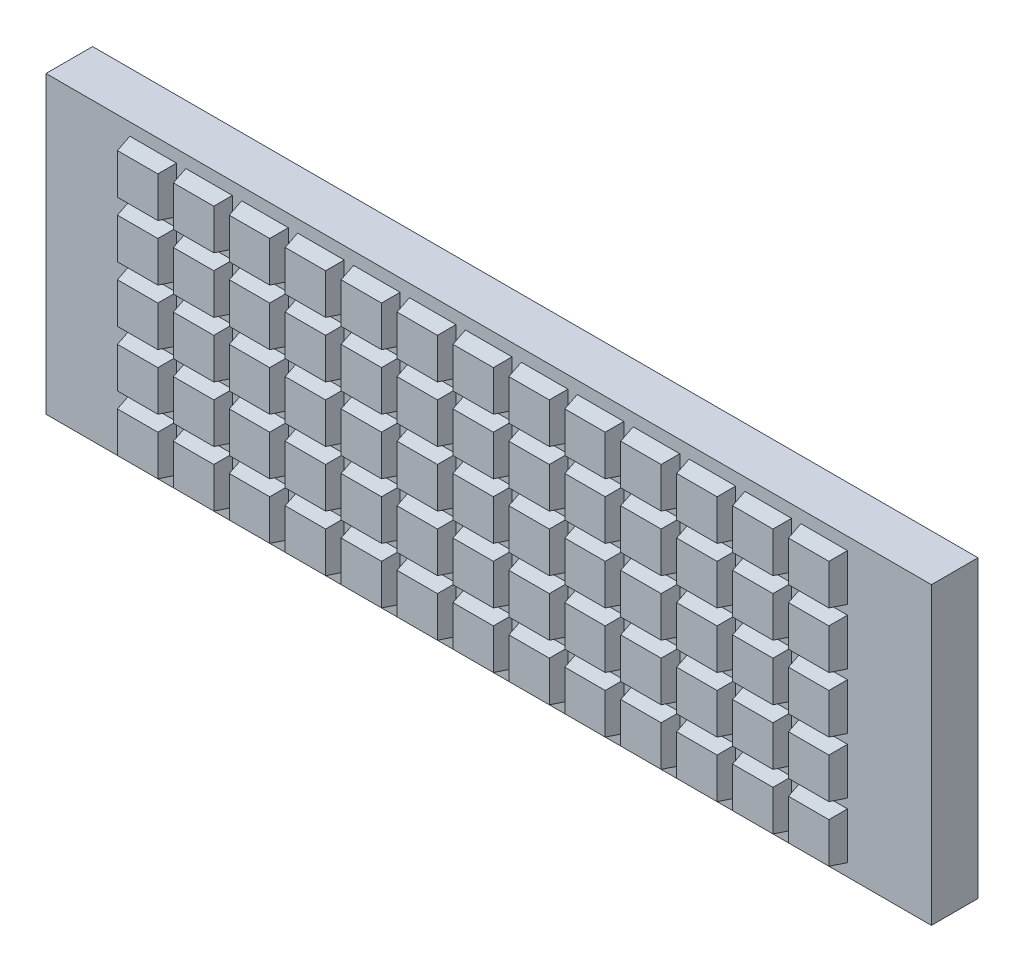
SolidWorks part; units mm, degrees
ref_plane "前视基准面" through (0, 0, 0) normal (0, 0, 1) x (1, 0, 0)
ref_plane "上视基准面" through (0, 0, 0) normal (0, 1, 0) x (1, 0, 0)
ref_plane "右视基准面" through (0, 0, 0) normal (1, 0, 0) x (0, 0, -1)
sketch "草图1" plane through (0, 0, 0) normal (0, 0, 1) x (1, 0, 0)
  line L0 (-142.5, -47.5) -> (142.5, -47.5)
  line L1 (142.5, -47.5) -> (142.5, 47.5)
  line L2 (142.5, 47.5) -> (-142.5, 47.5)
  line L3 (-142.5, 47.5) -> (-142.5, -47.5)
extrude "凸台-拉伸1" add sketch "草图1" along normal blind 15
ref_plane "基准面1" through (0, 0, 15) normal (0, 0, 1) x (1, 0, 0)
ref_plane "基准面2" through (0, 0, 20) normal (0, 0, 1) x (1, 0, 0)
sketch "草图2" plane through (0, 0, 15) normal (0, 0, 1) x (1, 0, 0)
  line L0 (-115.5, -43.5) -> (-100.5, -43.5)
  line L1 (-100.5, -43.5) -> (-100.5, -28.5)
  line L2 (-100.5, -28.5) -> (-115.5, -28.5)
  line L3 (-115.5, -28.5) -> (-115.5, -43.5)
sketch "草图3" plane through (0, 0, 20) normal (0, 0, 1) x (1, 0, 0)
  line L0 (-114.5, -42.5) -> (-101.5, -42.5)
  line L1 (-101.5, -42.5) -> (-101.5, -29.5)
  line L2 (-101.5, -29.5) -> (-114.5, -29.5)
  line L3 (-114.5, -29.5) -> (-114.5, -42.5)
loft "放样1" add profiles "草图2", "草图3"
pattern_linear "阵列(线性)1" count 13 spacing 18 along (1, 0, 0) count 5 spacing 18 along (0, 1, 0) of "放样1"
